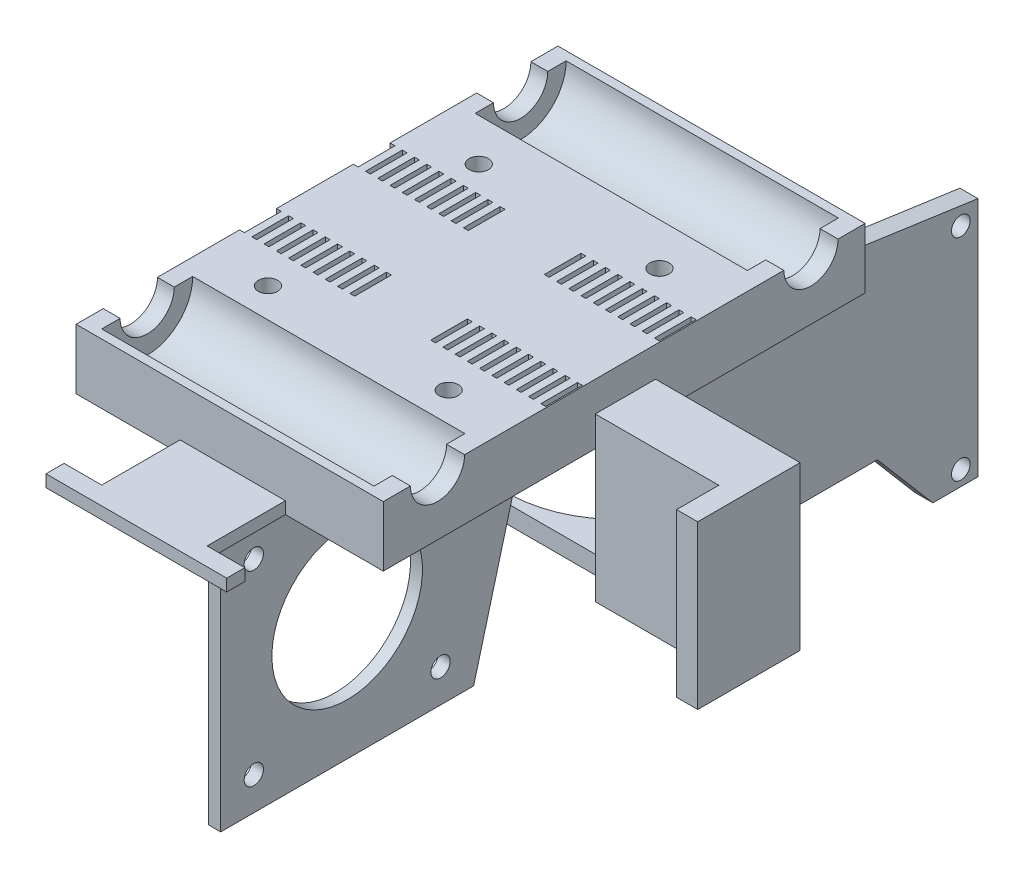
SolidWorks part; units mm, degrees
ref_plane "Front Plane" through (0, 0, 0) normal (0, 0, 1) x (1, 0, 0)
ref_plane "Top Plane" through (0, 0, 0) normal (0, 1, 0) x (1, 0, 0)
ref_plane "Right Plane" through (0, 0, 0) normal (1, 0, 0) x (0, 0, -1)
sketch "Sketch2" plane through (0, 0, 0) normal (0, 1, 0) x (1, 0, 0)
  line L0 (0, 0) -> (0, 80)
  line L1 (0, 80) -> (51, 80)
  line L2 (51, 80) -> (51, 0)
  line L3 (51, 0) -> (0, 0)
  dimension "D1" = 51
  dimension "D2" = 80
extrude "Boss-Extrude1" add sketch "Sketch2" along normal blind 10
ref_plane "Plane2" through (48, 0, 0) normal (1, 0, 0) x (0, 0, -1)
sketch "Sketch4" plane through (48, 0, 0) normal (1, 0, 0) x (0, 0, -1)
  line L0 (0, 10) -> (80, 10) construction
  line L1 (0, 10) -> (0, 0) construction
  line L2 (80, 10) -> (80, 0) construction
  circle A0 centre (9, 10) radius 7.55
  circle A1 centre (71, 10) radius 7.55
  dimension "D1" = 15.1
  dimension "D3" = 15.1
  dimension "D2" = 9
  dimension "D4" = 9
extrude "Cut-Extrude1" cut sketch "Sketch4" against normal blind 45.2
sketch "Sketch5" plane through (51, 0, 0) normal (1, 0, 0) x (0, 0, -1)
  line L0 (0, 10) -> (80, 10) construction
  circle A0 centre (9, 10) radius 4.5
  circle A1 centre (71, 10) radius 4.5
  arc A2 (1.45, 10) -> (16.55, 10) centre (9, 10) ccw construction
  arc A3 (63.45, 10) -> (78.55, 10) centre (71, 10) ccw construction
  dimension "D1" = 9
extrude "Cut-Extrude2" cut sketch "Sketch5" against normal through all
sketch "Sketch6" plane through (0, 10, 0) normal (0, 1, 0) x (1, 0, 0)
  line L0 (48, 63.45) -> (2.8, 63.45) construction
  line L1 (25.4, 63.45) -> (25.4, 31.4731) construction
  circle A0 centre (10.4, 56.45) radius 1.6
  circle A1 centre (40.4, 56.45) radius 1.6
  circle A2 centre (10.4, 21.45) radius 1.6
  circle A3 centre (40.4, 21.45) radius 1.6
  dimension "D1" = 3.2
  dimension "D2" = 7
  dimension "D3" = 35
  dimension "D4" = 30
  dimension "D5" = 15
extrude "Cut-Extrude3" cut sketch "Sketch6" against normal blind 45.1
sketch "Sketch9" plane through (0, 0, 0) normal (0, -1, 0) x (1, 0, 0)
  circle A0 centre (4.9, -70.26) radius 1.1
  circle A1 centre (4.9, -76.96) radius 1.1
  dimension "D1" = 2.2
extrude "Cut-Extrude4" cut sketch "Sketch9" against normal blind 1.5
sketch "Sketch10" plane through (0, 0, 0) normal (0, -1, 0) x (1, 0, 0)
  line L1 (13.6332, -21.45) -> (12.0166, -18.65)
  line L2 (12.0166, -18.65) -> (8.7834, -18.65)
  line L3 (8.7834, -18.65) -> (7.1668, -21.45)
  line L4 (7.1668, -21.45) -> (8.7834, -24.25)
  line L5 (8.7834, -24.25) -> (12.0166, -24.25)
  line L6 (12.0166, -24.25) -> (13.6332, -21.45)
  line L7 (43.6332, -21.45) -> (42.0166, -18.65)
  line L8 (42.0166, -18.65) -> (38.7834, -18.65)
  line L9 (38.7834, -18.65) -> (37.1668, -21.45)
  line L10 (37.1668, -21.45) -> (38.7834, -24.25)
  line L11 (38.7834, -24.25) -> (42.0166, -24.25)
  line L12 (42.0166, -24.25) -> (43.6332, -21.45)
  line L13 (13.6332, -56.45) -> (12.0166, -53.65)
  line L14 (12.0166, -53.65) -> (8.7834, -53.65)
  line L15 (8.7834, -53.65) -> (7.1668, -56.45)
  line L16 (7.1668, -56.45) -> (8.7834, -59.25)
  line L17 (8.7834, -59.25) -> (12.0166, -59.25)
  line L18 (12.0166, -59.25) -> (13.6332, -56.45)
  line L19 (43.6332, -56.45) -> (42.0166, -53.65)
  line L20 (42.0166, -53.65) -> (38.7834, -53.65)
  line L21 (38.7834, -53.65) -> (37.1668, -56.45)
  line L22 (37.1668, -56.45) -> (38.7834, -59.25)
  line L23 (38.7834, -59.25) -> (42.0166, -59.25)
  line L24 (42.0166, -59.25) -> (43.6332, -56.45)
  circle A0 centre (10.4, -21.45) radius 2.8 construction
  circle A1 centre (40.4, -21.45) radius 2.8 construction
  circle A2 centre (10.4, -56.45) radius 2.8 construction
  circle A3 centre (10.4, -56.45) radius 1.6 construction
  circle A4 centre (40.4, -56.45) radius 2.8 construction
  circle A5 centre (40.4, -56.45) radius 1.6 construction
  point P10 (7.9751, -22.85)
  dimension "D1" = 5.6
  dimension "D2" = 5.6
extrude "Cut-Extrude5" cut sketch "Sketch10" against normal blind 2.3 and the other way blind 5
ref_plane "Plane3" through (0, 0, -40.63) normal (0, 0, -1) x (-1, 0, 0)
sketch "Sketch12" plane through (0, 10, 0) normal (0, 1, 0) x (1, 0, 0)
  line L0 (0.8, 46.02) -> (0, 46.02)
  line L1 (51, 80) -> (0, 80) construction
  line L2 (0, 46.02) -> (0, 52.12)
  line L3 (0, 66.5) -> (0, 13.5) construction
  line L4 (0.8, 46.02) -> (0.8, 52.12)
  line L5 (0.8, 52.12) -> (0, 52.12)
  line L6 (0.8, 33.25) -> (0, 33.25)
  line L7 (0, 33.25) -> (0, 27.15)
  line L8 (0, 27.15) -> (0.8, 27.15)
  line L9 (0.8, 27.15) -> (0.8, 33.25)
  line L10 (2.832, 33.25) -> (2.032, 33.25)
  line L11 (2.832, 46.02) -> (2.032, 46.02)
  line L12 (2.032, 33.25) -> (2.032, 27.15)
  line L13 (2.832, 27.15) -> (2.832, 33.25)
  line L14 (2.032, 27.15) -> (2.832, 27.15)
  line L15 (2.832, 46.02) -> (2.832, 52.12)
  line L16 (2.032, 46.02) -> (2.032, 52.12)
  line L17 (2.832, 52.12) -> (2.032, 52.12)
  line L18 (4.864, 33.25) -> (4.064, 33.25)
  line L19 (4.864, 46.02) -> (4.064, 46.02)
  line L20 (4.064, 33.25) -> (4.064, 27.15)
  line L21 (4.864, 27.15) -> (4.864, 33.25)
  line L22 (4.064, 27.15) -> (4.864, 27.15)
  line L23 (4.864, 46.02) -> (4.864, 52.12)
  line L24 (4.064, 46.02) -> (4.064, 52.12)
  line L25 (4.864, 52.12) -> (4.064, 52.12)
  line L26 (6.896, 33.25) -> (6.096, 33.25)
  line L27 (6.896, 46.02) -> (6.096, 46.02)
  line L28 (6.096, 33.25) -> (6.096, 27.15)
  line L29 (6.896, 27.15) -> (6.896, 33.25)
  line L30 (6.096, 27.15) -> (6.896, 27.15)
  line L31 (6.896, 46.02) -> (6.896, 52.12)
  line L32 (6.096, 46.02) -> (6.096, 52.12)
  line L33 (6.896, 52.12) -> (6.096, 52.12)
  line L34 (8.928, 33.25) -> (8.128, 33.25)
  line L35 (8.928, 46.02) -> (8.128, 46.02)
  line L36 (8.128, 33.25) -> (8.128, 27.15)
  line L37 (8.928, 27.15) -> (8.928, 33.25)
  line L38 (8.128, 27.15) -> (8.928, 27.15)
  line L39 (8.928, 46.02) -> (8.928, 52.12)
  line L40 (8.128, 46.02) -> (8.128, 52.12)
  line L41 (8.928, 52.12) -> (8.128, 52.12)
  line L42 (10.96, 33.25) -> (10.16, 33.25)
  line L43 (10.96, 46.02) -> (10.16, 46.02)
  line L44 (10.16, 33.25) -> (10.16, 27.15)
  line L45 (10.96, 27.15) -> (10.96, 33.25)
  line L46 (10.16, 27.15) -> (10.96, 27.15)
  line L47 (10.96, 46.02) -> (10.96, 52.12)
  line L48 (10.16, 46.02) -> (10.16, 52.12)
  line L49 (10.96, 52.12) -> (10.16, 52.12)
  line L50 (12.992, 33.25) -> (12.192, 33.25)
  line L51 (12.992, 46.02) -> (12.192, 46.02)
  line L52 (12.192, 33.25) -> (12.192, 27.15)
  line L53 (12.992, 27.15) -> (12.992, 33.25)
  line L54 (12.192, 27.15) -> (12.992, 27.15)
  line L55 (12.992, 46.02) -> (12.992, 52.12)
  line L56 (12.192, 46.02) -> (12.192, 52.12)
  line L57 (12.992, 52.12) -> (12.192, 52.12)
  line L58 (15.024, 33.25) -> (14.224, 33.25)
  line L59 (15.024, 46.02) -> (14.224, 46.02)
  line L60 (14.224, 33.25) -> (14.224, 27.15)
  line L61 (15.024, 27.15) -> (15.024, 33.25)
  line L62 (14.224, 27.15) -> (15.024, 27.15)
  line L63 (15.024, 46.02) -> (15.024, 52.12)
  line L64 (14.224, 46.02) -> (14.224, 52.12)
  line L65 (15.024, 52.12) -> (14.224, 52.12)
  line L66 (17.056, 33.25) -> (16.256, 33.25)
  line L67 (17.056, 46.02) -> (16.256, 46.02)
  line L68 (16.256, 33.25) -> (16.256, 27.15)
  line L69 (17.056, 27.15) -> (17.056, 33.25)
  line L70 (16.256, 27.15) -> (17.056, 27.15)
  line L71 (17.056, 46.02) -> (17.056, 52.12)
  line L72 (16.256, 46.02) -> (16.256, 52.12)
  line L73 (17.056, 52.12) -> (16.256, 52.12)
  line L74 (19.088, 33.25) -> (18.288, 33.25)
  line L75 (19.088, 46.02) -> (18.288, 46.02)
  line L76 (18.288, 33.25) -> (18.288, 27.15)
  line L77 (19.088, 27.15) -> (19.088, 33.25)
  line L78 (18.288, 27.15) -> (19.088, 27.15)
  line L79 (19.088, 46.02) -> (19.088, 52.12)
  line L80 (18.288, 46.02) -> (18.288, 52.12)
  line L81 (19.088, 52.12) -> (18.288, 52.12)
  line L82 (25.4, 63.45) -> (25.4, 16.55) construction
  line L83 (48, 63.45) -> (2.8, 63.45) construction
  line L84 (2.8, 16.55) -> (48, 16.55) construction
  line L85 (31.712, 27.15) -> (31.712, 33.25)
  line L86 (32.512, 27.15) -> (31.712, 27.15)
  line L87 (32.512, 33.25) -> (32.512, 27.15)
  line L88 (31.712, 33.25) -> (32.512, 33.25)
  line L89 (33.744, 27.15) -> (33.744, 33.25)
  line L90 (34.544, 27.15) -> (33.744, 27.15)
  line L91 (34.544, 33.25) -> (34.544, 27.15)
  line L92 (33.744, 33.25) -> (34.544, 33.25)
  line L93 (35.776, 27.15) -> (35.776, 33.25)
  line L94 (36.576, 27.15) -> (35.776, 27.15)
  line L95 (36.576, 33.25) -> (36.576, 27.15)
  line L96 (35.776, 33.25) -> (36.576, 33.25)
  line L97 (37.808, 27.15) -> (37.808, 33.25)
  line L98 (38.608, 27.15) -> (37.808, 27.15)
  line L99 (38.608, 33.25) -> (38.608, 27.15)
  line L100 (37.808, 33.25) -> (38.608, 33.25)
  line L101 (39.84, 27.15) -> (39.84, 33.25)
  line L102 (40.64, 27.15) -> (39.84, 27.15)
  line L103 (40.64, 33.25) -> (40.64, 27.15)
  line L104 (39.84, 33.25) -> (40.64, 33.25)
  line L105 (41.872, 27.15) -> (41.872, 33.25)
  line L106 (42.672, 27.15) -> (41.872, 27.15)
  line L107 (42.672, 33.25) -> (42.672, 27.15)
  line L108 (41.872, 33.25) -> (42.672, 33.25)
  line L109 (43.904, 27.15) -> (43.904, 33.25)
  line L110 (44.704, 27.15) -> (43.904, 27.15)
  line L111 (44.704, 33.25) -> (44.704, 27.15)
  line L112 (43.904, 33.25) -> (44.704, 33.25)
  line L113 (45.936, 27.15) -> (45.936, 33.25)
  line L114 (46.736, 27.15) -> (45.936, 27.15)
  line L115 (46.736, 33.25) -> (46.736, 27.15)
  line L116 (45.936, 33.25) -> (46.736, 33.25)
  line L117 (47.968, 27.15) -> (47.968, 33.25)
  line L118 (48.768, 27.15) -> (47.968, 27.15)
  line L119 (48.768, 33.25) -> (48.768, 27.15)
  line L120 (47.968, 33.25) -> (48.768, 33.25)
  line L121 (50.8, 27.15) -> (50, 27.15)
  line L122 (50.8, 33.25) -> (50.8, 27.15)
  line L123 (50, 33.25) -> (50.8, 33.25)
  line L124 (50, 27.15) -> (50, 33.25)
  line L125 (47.968, 46.02) -> (47.968, 52.12)
  line L126 (47.968, 52.12) -> (48.768, 52.12)
  line L127 (48.768, 46.02) -> (48.768, 52.12)
  line L128 (47.968, 46.02) -> (48.768, 46.02)
  line L129 (39.84, 46.02) -> (39.84, 52.12)
  line L130 (39.84, 52.12) -> (40.64, 52.12)
  line L131 (40.64, 46.02) -> (40.64, 52.12)
  line L132 (39.84, 46.02) -> (40.64, 46.02)
  line L133 (41.872, 46.02) -> (41.872, 52.12)
  line L134 (41.872, 52.12) -> (42.672, 52.12)
  line L135 (42.672, 46.02) -> (42.672, 52.12)
  line L136 (41.872, 46.02) -> (42.672, 46.02)
  line L137 (31.712, 46.02) -> (31.712, 52.12)
  line L138 (31.712, 52.12) -> (32.512, 52.12)
  line L139 (32.512, 46.02) -> (32.512, 52.12)
  line L140 (31.712, 46.02) -> (32.512, 46.02)
  line L141 (33.744, 46.02) -> (33.744, 52.12)
  line L142 (33.744, 52.12) -> (34.544, 52.12)
  line L143 (34.544, 46.02) -> (34.544, 52.12)
  line L144 (33.744, 46.02) -> (34.544, 46.02)
  line L145 (35.776, 46.02) -> (35.776, 52.12)
  line L146 (35.776, 52.12) -> (36.576, 52.12)
  line L147 (36.576, 46.02) -> (36.576, 52.12)
  line L148 (35.776, 46.02) -> (36.576, 46.02)
  line L149 (37.808, 46.02) -> (37.808, 52.12)
  line L150 (37.808, 52.12) -> (38.608, 52.12)
  line L151 (38.608, 46.02) -> (38.608, 52.12)
  line L152 (37.808, 46.02) -> (38.608, 46.02)
  line L153 (43.904, 46.02) -> (43.904, 52.12)
  line L154 (43.904, 52.12) -> (44.704, 52.12)
  line L155 (44.704, 46.02) -> (44.704, 52.12)
  line L156 (43.904, 46.02) -> (44.704, 46.02)
  line L157 (45.936, 46.02) -> (45.936, 52.12)
  line L158 (45.936, 52.12) -> (46.736, 52.12)
  line L159 (46.736, 46.02) -> (46.736, 52.12)
  line L160 (45.936, 46.02) -> (46.736, 46.02)
  line L161 (50, 46.02) -> (50, 52.12)
  line L162 (50, 46.02) -> (50.8, 46.02)
  line L163 (50.8, 46.02) -> (50.8, 52.12)
  line L164 (50, 52.12) -> (50.8, 52.12)
  dimension "D1" = 0.8
  dimension "D2" = 33.98
  dimension "D3" = 6.1
  dimension "D4" = 52.85
  dimension "D5" = 6.1
  dimension "D6" = 10
extrude "Cut-Extrude6" cut sketch "Sketch12" against normal blind 0.8
sketch "Sketch13" plane through (0, 0, 0) normal (0, -1, 0) x (1, 0, 0)
  line L0 (17.25, 0) -> (17.25, 13)
  line L1 (0, 0) -> (51, 0) construction
  line L2 (17.25, 13) -> (11, 13)
  line L3 (11, 13) -> (11, 16)
  line L4 (11, 16) -> (41, 16)
  line L5 (41, 16) -> (41, 13)
  line L6 (34.75, 13) -> (34.75, 0)
  line L7 (41, 13) -> (34.75, 13)
  line L8 (17.25, 0) -> (34.75, 0)
  line L9 (51, 0) -> (51, -80) construction
  point P4 (26, 0)
  point P13 (26, 16)
  dimension "D1" = 3
  dimension "D2" = 13
  dimension "D3" = 30
  dimension "D4" = 17.5
  dimension "D5" = 25
extrude "Boss-Extrude4" add sketch "Sketch13" against normal blind 2
ref_plane "Plane4" through (31, 0, 0) normal (1, 0, 0) x (0, 0, -1)
sketch "Sketch14" plane through (31, 0, 0) normal (1, 0, 0) x (0, 0, -1)
  line L0 (46.7898, 0) -> (35, -44)
  line L1 (0, 0) -> (80, 0) construction
  line L4 (-7, -2) -> (-7, -44)
  line L5 (-7, -44) -> (35, -44)
  line L7 (-7, -2) -> (-7, 0)
  line L8 (46.7898, 0) -> (-7, 0)
  line L9 (0, 10) -> (0, 0) construction
  circle A0 centre (-1.5, -7.5) radius 1.6
  circle A1 centre (29.5, -7.5) radius 1.6
  circle A2 centre (29.5, -38.5) radius 1.6
  circle A3 centre (-1.5, -38.5) radius 1.6
  dimension "D9" = 3.2
  dimension "D1" = 42
  dimension "D2" = 42
  dimension "D3" = 2
  dimension "D4" = 75
  dimension "D5" = 31
  dimension "D6" = 31
  dimension "D7" = 5.5
  dimension "D8" = 5.5
  dimension "D10" = 7
extrude "Boss-Extrude5" add sketch "Sketch14" against normal blind 2
sketch "Sketch15" plane through (0, 0, 0) normal (0, -1, 0) x (1, 0, 0)
  line L0 (0, -80) -> (0, 0) construction
  line L1 (9.955, -63.0275) -> (29.955, -63.0275)
  line L2 (9.955, -63.0275) -> (9.955, -73.0275)
  line L3 (9.955, -73.0275) -> (29.955, -73.0275)
  line L4 (29.955, -63.0275) -> (29.955, -73.0275)
  line L5 (51, -80) -> (0, -80) construction
  circle A0 centre (26.955, -67.1275) radius 1.55
  circle A1 centre (12.955, -67.1275) radius 1.55
  dimension "D6" = 3.1
  dimension "D1" = 9.955
  dimension "D2" = 20
  dimension "D3" = 10
  dimension "D4" = 4.1
  dimension "D5" = 14
  dimension "D7" = 6.9725
  dimension "D8" = 3
extrude "Boss-Extrude6" add sketch "Sketch15" along normal blind 10.9
ref_plane "Plane5" through (0, -33, 0) normal (0, -1, 0) x (-1, 0, 0)
sketch "Sketch16" plane through (0, -33, 0) normal (0, -1, 0) x (-1, 0, 0)
  line L0 (-40, 50.0275) -> (-40, 90.0275)
  line L1 (-40, 90.0275) -> (-20, 90.0275)
  line L2 (-40, 50.0275) -> (0, 50.0275)
  line L3 (0, 50.0275) -> (0, 70.0275)
  line L4 (-20, 90.0275) -> (-20, 88.5275)
  line L5 (0, 70.0275) -> (-1.5, 70.0275)
  line L6 (0, 0) -> (-17.25, 0) construction
  line L7 (-51, 0) -> (-51, 80) construction
  line L8 (0, 80) -> (0, 0) construction
  circle A0 centre (-36, 86.0275) radius 1.6
  circle A1 centre (-4, 54.0275) radius 1.6
  circle A2 centre (-36, 54.0275) radius 1.6
  arc A3 (-20, 88.5275) -> (-1.5, 70.0275) centre (-20, 70.0275) ccw
  dimension "D1" = 37
  dimension "D8" = 3.2
  dimension "D2" = 20
  dimension "D3" = 20
  dimension "D4" = 50.0275
  dimension "D5" = 11
  dimension "D6" = 4
  dimension "D7" = 4
  dimension "D9" = 40
  dimension "D10" = 32
  dimension "D11" = 32
extrude "Boss-Extrude7" add sketch "Sketch16" against normal blind 3 separate body
sketch "Sketch17" plane through (0, 0, -50.0275) normal (0, 0, 1) x (1, 0, 0)
  line L0 (0, -33) -> (8, -33)
  line L1 (40, -33) -> (0, -33) construction
  line L2 (8, -33) -> (0, -33)
  line L3 (0, -33) -> (0, 0)
  line L4 (8, -33) -> (8, 0)
  line L5 (8, 0) -> (0, 0)
  line M3 (0, -33) -> (40, -33)
  line M5 (40, -30) -> (0, -30)
  line M6 (0, -30) -> (0, -33)
  dimension "D1" = 8
extrude "Boss-Extrude8" add sketch "Sketch17" along normal blind 2 contours L4 L5 L3 M5 | L4 M3 M5 M6
sketch "Sketch18" plane through (40, 0, 0) normal (1, 0, 0) x (0, 0, -1)
  line L0 (50.0275, -33) -> (50.0275, 0)
  line L1 (0, 0) -> (80, 0) construction
  line L2 (50.0275, -33) -> (90.0275, -33)
  line L3 (90.0275, -33) -> (50.0275, -33) construction
  line L6 (90.0275, -30) -> (90.0275, -33) construction
  line L9 (50.0275, 0) -> (80, 0)
  line L10 (80, 10) -> (80, 0) construction
  line L11 (80, 0) -> (106.734, -3.8)
  line L12 (106.734, -3.8) -> (106.734, -43.8)
  line L13 (106.734, -43.8) -> (99.234, -43.8)
  line L14 (99.234, -43.8) -> (90.0275, -33)
  circle A0 centre (68.8775, -6.297) radius 1.55
  circle A1 centre (103.8775, -6.297) radius 1.55
  circle A2 centre (103.8775, -41.297) radius 1.55
  dimension "D8" = 3.1
  dimension "D1" = 35
  dimension "D2" = 40
  dimension "D3" = 35
  dimension "D4" = 3.8
  dimension "D5" = 2.8565
  dimension "D6" = 6.297
  dimension "D7" = 19.874
  dimension "D9" = 7.5
extrude "Boss-Extrude9" add sketch "Sketch18" along normal blind 3
sketch "Sketch20" plane through (0, 0, 0) normal (0, -1, 0) x (1, 0, 0)
  line L6 (42.0166, -59.25) -> (43.6332, -56.45)
  line L7 (43.6332, -56.45) -> (42.0166, -53.65)
  line L8 (42.0166, -53.65) -> (38.7834, -53.65)
  line L9 (38.7834, -53.65) -> (37.1668, -56.45)
  line L10 (37.1668, -56.45) -> (38.7834, -59.25)
  line L11 (38.7834, -59.25) -> (42.0166, -59.25)
  line L12 (42.0166, -59.25) -> (43.6332, -56.45)
  line L13 (43.6332, -56.45) -> (42.0166, -53.65)
  line L14 (42.0166, -53.65) -> (38.7834, -53.65)
  line L15 (38.7834, -53.65) -> (37.1668, -56.45)
  line L16 (37.1668, -56.45) -> (38.7834, -59.25)
  line L17 (38.7834, -59.25) -> (42.0166, -59.25)
  dimension "D1" = 0
extrude "Cut-Extrude9" cut sketch "Sketch20" along normal offset from surface (6 mm away) 27 up to face at (20.5831, -33, -67.2444)
ref_plane "Plane6" through (0, 5, 0) normal (0, -1, 0) x (-1, 0, 0)
sketch "Sketch21" plane through (0, 5, 0) normal (0, -1, 0) x (-1, 0, 0)
  line L0 (-71.5, 35.2) -> (-51, 35.2)
  line L1 (-71.5, 35.2) -> (-71.5, 28.2)
  line L2 (-71.5, 28.2) -> (-75, 28.2)
  line L3 (-75, 28.2) -> (-75, 45.2)
  line L4 (-75, 45.2) -> (-51, 45.2)
  line L5 (-51, 0) -> (-51, 80) construction
  line L6 (-51, 45.2) -> (-51, 35.2)
  line L7 (-34.75, 0) -> (-51, 0) construction
  dimension "D1" = 35.2
  dimension "D2" = 20.5
  dimension "D3" = 3.5
  dimension "D4" = 10
  dimension "D5" = 17
extrude "Boss-Extrude10" add sketch "Sketch21" along normal blind 27
sketch "Sketch22" plane through (29, 0, 0) normal (-1, 0, 0) x (0, 0, 1)
  line L0 (-29.5, -5.9) -> (-29.5, -40.1) construction
  line L1 (-31.1, -38.5) -> (3.1, -38.5) construction
  circle A0 centre (-14, -23) radius 12.5
  circle A1 centre (-29.5, -7.5) radius 1.6 construction
  circle A2 centre (-29.5, -38.5) radius 1.6 construction
  circle A3 centre (1.5, -38.5) radius 1.6 construction
  point P14 (-29.5, -23)
  point P15 (-14, -38.5)
  dimension "D1" = 25
extrude "Cut-Extrude10" cut sketch "Sketch22" against normal blind 10
ref_plane "Plane7" through (0, -5.9, 0) normal (0, -1, 0) x (-1, 0, 0)
sketch "Sketch23" plane through (0, -5.9, 0) normal (0, -1, 0) x (-1, 0, 0)
  line L1 (-16.1882, 67.1275) -> (-14.5716, 64.3275)
  line L2 (-14.5716, 64.3275) -> (-11.3384, 64.3275)
  line L3 (-11.3384, 64.3275) -> (-9.7218, 67.1275)
  line L4 (-9.7218, 67.1275) -> (-11.3384, 69.9275)
  line L5 (-11.3384, 69.9275) -> (-14.5716, 69.9275)
  line L6 (-14.5716, 69.9275) -> (-16.1882, 67.1275)
  line L7 (-23.7218, 67.1275) -> (-25.3384, 69.9275)
  line L8 (-25.3384, 69.9275) -> (-28.5716, 69.9275)
  line L9 (-28.5716, 69.9275) -> (-30.1882, 67.1275)
  line L10 (-30.1882, 67.1275) -> (-28.5716, 64.3275)
  line L11 (-28.5716, 64.3275) -> (-25.3384, 64.3275)
  line L12 (-25.3384, 64.3275) -> (-23.7218, 67.1275)
  circle A0 centre (-12.955, 67.1275) radius 2.8 construction
  circle A1 centre (-26.955, 67.1275) radius 2.8 construction
  circle A2 centre (-12.955, 67.1275) radius 1.55 construction
  circle A3 centre (-26.955, 67.1275) radius 1.55 construction
  dimension "D1" = 5.6
extrude "Cut-Extrude11" cut sketch "Sketch23" against normal through all
